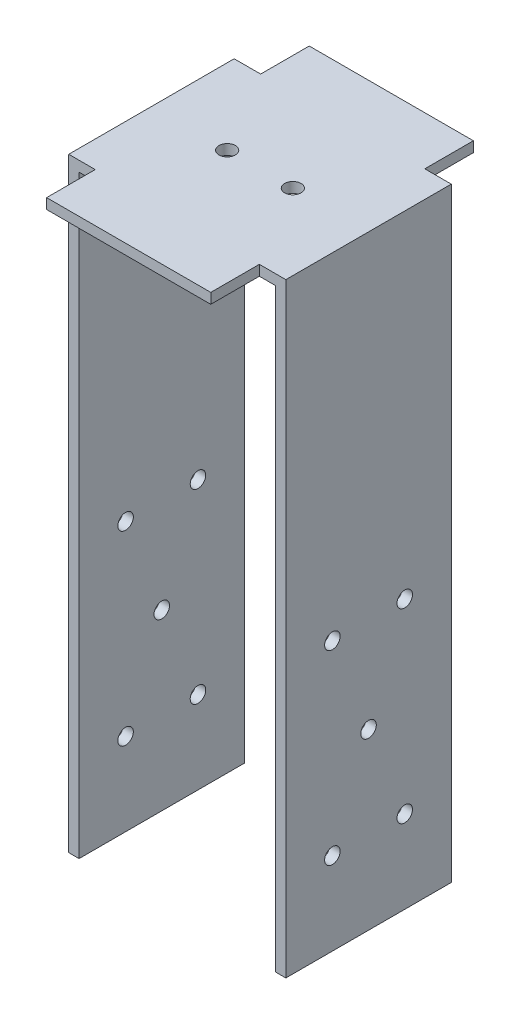
SolidWorks part; units mm, degrees
material "Galvanized Steel"
ref_plane "Front Plane" through (0, 0, 0) normal (0, 0, 1) x (1, 0, 0)
ref_plane "Top Plane" through (0, 0, 0) normal (0, 1, 0) x (1, 0, 0)
ref_plane "Right Plane" through (0, 0, 0) normal (1, 0, 0) x (0, 0, -1)
sketch "Sketch1" plane through (0, 0, 0) normal (0, 1, 0) x (1, 0, 0)
  line L0 (-21, 16) -> (-15.875, 16)
  line L1 (-15.875, 16) -> (-15.875, 25.4)
  line L2 (-15.875, 25.4) -> (15.875, 25.4)
  line L3 (15.875, 25.4) -> (15.875, 16)
  line L4 (15.875, 16) -> (21, 16)
  line L5 (21, 16) -> (21, -16)
  line L6 (21, -16) -> (15.875, -16)
  line L7 (15.875, -16) -> (15.875, -25.4)
  line L8 (15.875, -25.4) -> (-15.875, -25.4)
  line L9 (-15.875, -25.4) -> (-15.875, -16)
  line L10 (-15.875, -16) -> (-21, -16)
  line L11 (-21, -16) -> (-21, 16)
  point P12 (-21, 0)
  point P13 (21, 0)
  point P15 (0, -25.4)
  point P16 (0, 25.4)
  dimension "D1" = 31.75
  dimension "D2" = 42
  dimension "D3" = 50.8
  dimension "D4" = 32
extrude "Boss-Extrude1" add sketch "Sketch1" against normal blind 2
sketch "Sketch2" plane through (0, -2, 0) normal (0, -1, 0) x (1, 0, 0)
  line L0 (-19, 16) -> (-19, -16)
  line L1 (-21, 16) -> (-15.875, 16) construction
  line L2 (-15.875, -16) -> (-21, -16) construction
  line L3 (19, 16) -> (19, -16)
  line L4 (15.875, 16) -> (21, 16) construction
  line L5 (21, -16) -> (15.875, -16) construction
  line L6 (-21, -16) -> (-21, 16) construction
  line L7 (21, 16) -> (21, -16) construction
  line L8 (-19, 16) -> (-21, 16)
  line L9 (-21, 16) -> (-21, -16)
  line L10 (-21, -16) -> (-19, -16)
  line L11 (19, 16) -> (21, 16)
  line L12 (21, 16) -> (21, -16)
  line L13 (21, -16) -> (19, -16)
  dimension "D1" = 2
  dimension "D2" = 2
extrude "Boss-Extrude2" add sketch "Sketch2" along normal blind 115
sketch "Sketch3" plane through (-21, 0, 0) normal (-1, 0, 0) x (0, 0, 1)
  line L0 (-16, -101) -> (16, -101) construction
  line L1 (-16, -117) -> (-16, 0) construction
  line L2 (16, -117) -> (16, 0) construction
  line L3 (-16, -65) -> (16, -65) construction
  line L4 (0, 0) -> (0, -117) construction
  line L5 (16, -117) -> (-16, -117) construction
  line L6 (-7, 0) -> (-7, -117) construction
  line L7 (-16, 0) -> (16, 0) construction
  line L8 (7, 0) -> (7, -117) construction
  circle A0 centre (-7, -65) radius 1.5
  circle A1 centre (7, -65) radius 1.5
  circle A2 centre (7, -101) radius 1.5
  circle A3 centre (-7, -101) radius 1.5
  circle A4 centre (0, -83.3365) radius 1.5
  dimension "D5" = 3
  dimension "D6" = 3
  dimension "D7" = 3
  dimension "D8" = 3
  dimension "D9" = 3
  dimension "D1" = 16
  dimension "D2" = 36
  dimension "D3" = 9
  dimension "D4" = 9
  dimension "D10" = 19
extrude "Cut-Extrude1" cut sketch "Sketch3" against normal through all
sketch "Sketch4" plane through (0, 0, 0) normal (0, 1, 0) x (1, 0, 0)
  line L2 (-15.875, 25.4) -> (-15.875, 16) construction
  line L3 (15.875, 16) -> (15.875, 25.4) construction
  circle A0 centre (-6.35, 0) radius 1.5875
  circle A1 centre (6.35, 0) radius 1.5875
  dimension "D1" = 3.175
  dimension "D2" = 3.175
  dimension "D3" = 9.525
  dimension "D4" = 9.525
extrude "Cut-Extrude2" cut sketch "Sketch4" against normal through all
